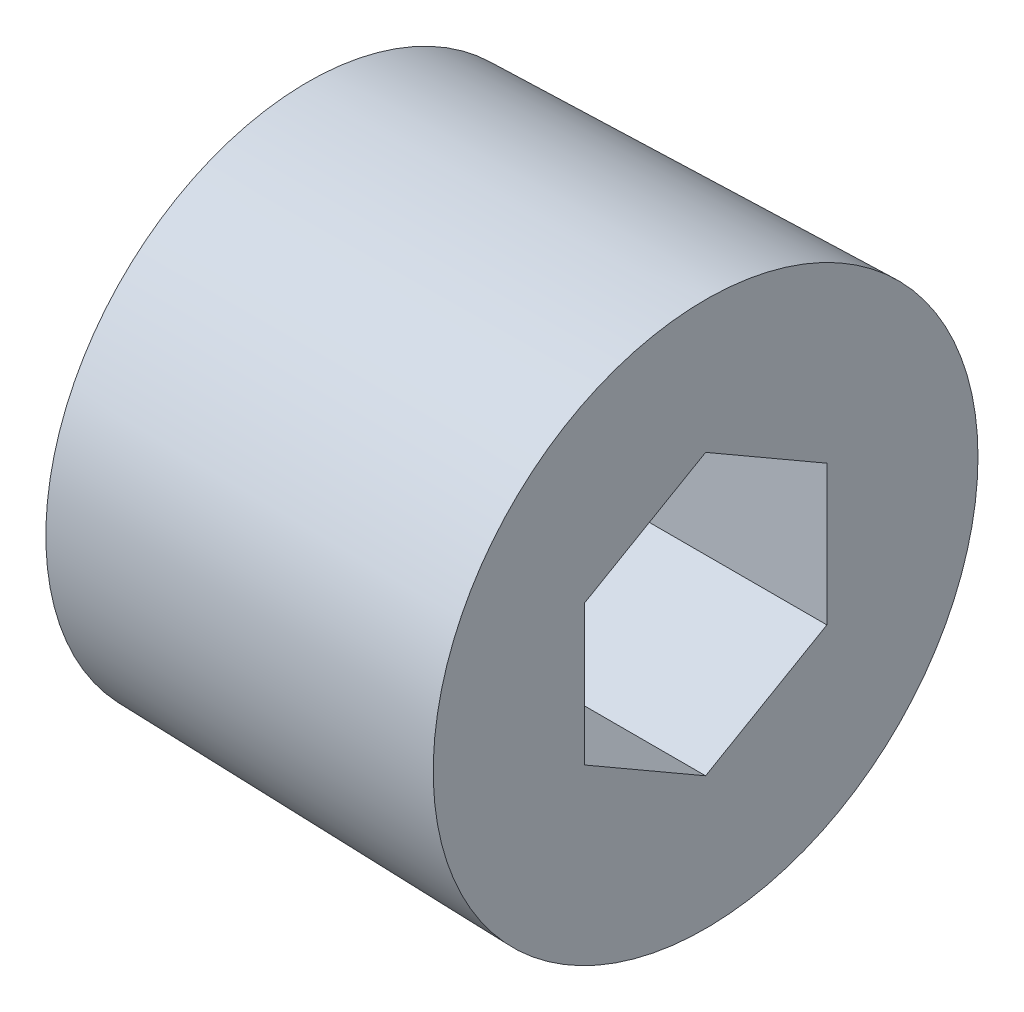
SolidWorks part; units mm, degrees
material "Chrome Stainless Steel"
ref_plane "Front" through (0, 0, 0) normal (0, 0, 1) x (1, 0, 0)
ref_plane "Top" through (0, 0, 0) normal (0, 1, 0) x (1, 0, 0)
ref_plane "Right" through (0, 0, 0) normal (1, 0, 0) x (0, 0, -1)
sketch "Sketch1" plane through (0, 0, 0) normal (0, 0, 1) x (1, 0, 0)
  line L0 (-5.207, 0) -> (5.207, 0) construction
  dimension "L" = 10.414
ref_plane "Plane1" through (-5.207, 0, 0) normal (1, 0, 0) x (0, 0, -1)
sketch "Sketch2" plane through (-5.207, 0, 0) normal (1, 0, 0) x (0, 0, -1)
  circle A0 centre (0, 0) radius 6.858
  dimension "OD" = 13.716
extrude "Extrude1" add sketch "Sketch2" along normal up to vertex (10.414 mm away) draft 1.5 up to point (5.207, 0, 0) draft outward yes
ref_plane "Plane2" through (5.207, 0, 0) normal (1, 0, 0) x (0, 0, -1)
ref_plane "Plane3" through (-2.1844, 0, 0) normal (1, 0, 0) x (0, 0, -1)
ref_plane "Plane4" through (4.6426, 0, 0) normal (1, 0, 0) x (0, 0, -1)
sketch "Sketch6" plane through (5.207, 0, 0) normal (1, 0, 0) x (0, 0, -1)
  line L1 (0, 3.6662) -> (-3.175, 1.8331)
  line L2 (-3.175, 1.8331) -> (-3.175, -1.8331)
  line L3 (-3.175, -1.8331) -> (0, -3.6662)
  line L4 (0, -3.6662) -> (3.175, -1.8331)
  line L5 (3.175, -1.8331) -> (3.175, 1.8331)
  line L6 (3.175, 1.8331) -> (0, 3.6662)
  circle A0 centre (0, 0) radius 3.175 construction
  dimension "Hex" = 6.35
extrude "Cut-Extrude7" cut sketch "Sketch6" against normal blind 5.5626
sketch "Sketch11" plane through (5.207, 0, 0) normal (1, 0, 0) x (0, 0, -1)
  circle A0 centre (0, 0) radius 3.6662
